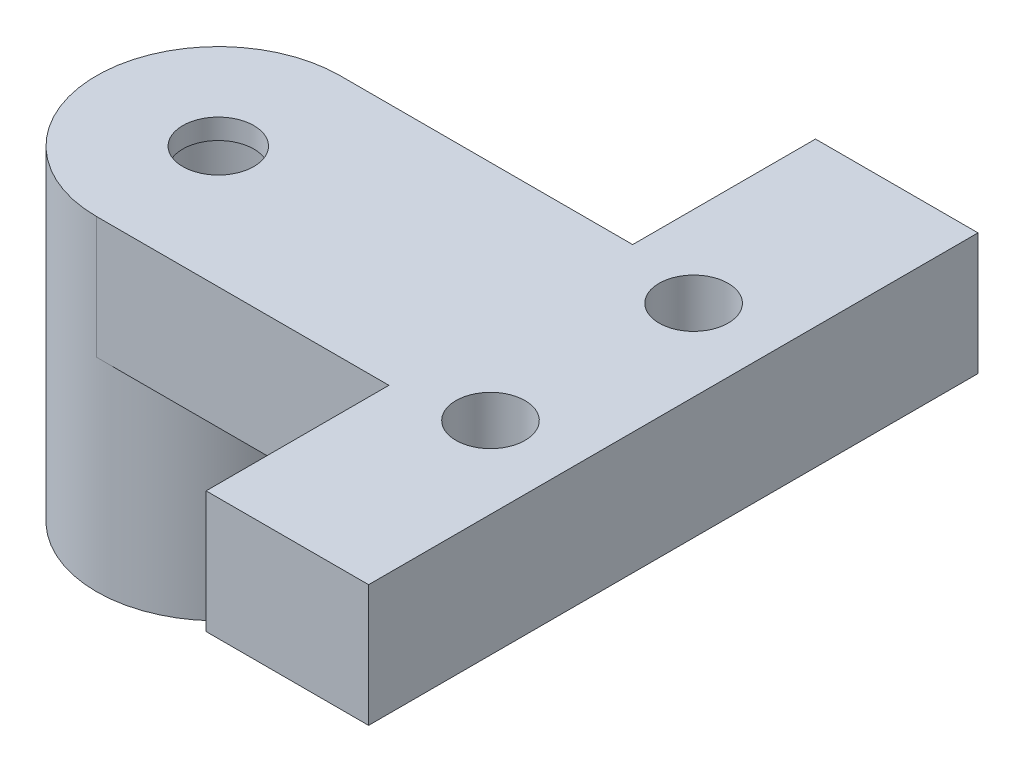
SolidWorks part; units mm, degrees
ref_plane "前视基准面" through (0, 0, 0) normal (0, 0, 1) x (1, 0, 0)
ref_plane "上视基准面" through (0, 0, 0) normal (0, 1, 0) x (1, 0, 0)
ref_plane "右视基准面" through (0, 0, 0) normal (1, 0, 0) x (0, 0, -1)
sketch "草图1" plane through (0, 0, 0) normal (0, 0, 1) x (1, 0, 0)
  line L1 (0, 0) -> (33, 0)
  line L2 (0, 0) -> (0, -6)
  line L3 (0, -6) -> (33, -6)
  line L4 (33, 0) -> (33, -6)
  dimension "D1" = 33
  dimension "D2" = 6
extrude "凸台-拉伸1" add sketch "草图1" along normal blind 30
sketch "草图3" plane through (0, -6, 0) normal (0, -1, 0) x (1, 0, 0)
  line L0 (0, 15) -> (33, 15) construction
  line L1 (0, 30) -> (0, 0) construction
  line L2 (33, 30) -> (33, 0) construction
  circle A0 centre (10.6, 15) radius 6
  dimension "D1" = 12
  dimension "D2" = 22.4
extrude "凸台-拉伸2" add sketch "草图3" along normal blind 10
sketch "草图4" plane through (0, -16, 0) normal (0, -1, 0) x (1, 0, 0)
  circle A0 centre (10.6, 15) radius 3.1
  dimension "D1" = 6.2
extrude "切除-拉伸1" cut sketch "草图4" against normal blind 15
sketch "草图5" plane through (0, -1, 0) normal (0, -1, 0) x (1, 0, 0)
  circle A0 centre (10.6, 15) radius 1.75
  dimension "D1" = 3.5
extrude "切除-拉伸2" cut sketch "草图5" against normal through all
sketch "草图10" plane through (0, 0, 0) normal (0, 0, 1) x (1, 0, 0)
  line L0 (10.6, -16) -> (10.6, 0) construction
  line L1 (4.6, -16) -> (16.6, -16) construction
  line L2 (33, 0) -> (0, 0) construction
  circle A0 centre (10.6, -11) radius 1
  dimension "D1" = 2
  dimension "D2" = 5
extrude "凸台-拉伸3" add sketch "草图10" along normal up to next
hole_wizard "M4 螺纹孔7" positions "3D草图8" profile "草图16" tap size "M4" standard "GB"
sketch3d "3D草图8"
  line L0 (10.6, -11, 9.0839) -> (10.6, -11, 0) construction
  point P0 (10.6, -11, 0)
cosmetic thread "孔螺蚊线7" parameters "D1"=11.3562, "D2"=4
sketch "草图16" plane through (10.6, -11, 0) normal (1, 0, 0) x (0, 1, 0)
  line L0 (0, 0) -> (0, 15.9914)
  line L1 (0, 15.9914) -> (1.65, 15)
  line L2 (1.65, 15) -> (1.65, 0)
  line L5 (1.65, 0) -> (0, 0)
  line L10 (0, 15.9914) -> (-1.65, 15) construction
  line L11 (0, -6.35) -> (0, 107.95) construction
  dimension "螺纹孔钻头直径" = 3.3
  dimension "螺纹孔钻头深度" = 15
  dimension "导头角度" = 118
sketch "草图17" plane through (0, 0, 0) normal (1, 0, 0) x (0, 0, -1)
  line L0 (-15, 5.4069) -> (-15, -30.5116) construction
  line L1 (-21, -16) -> (-9, -16) construction
  circle A0 centre (-15, -11) radius 1.5
  dimension "D1" = 3
  dimension "D2" = 5
extrude "凸台-拉伸4" add sketch "草图17" along normal up to next
hole_wizard "M4 螺纹孔8" positions "3D草图9" profile "草图18" tap size "M4" standard "GB"
sketch3d "3D草图9"
  line L0 (4.7905, -11, 15) -> (0, -11, 15) construction
  point P0 (0, -11, 15)
sketch "草图18" plane through (0, -11, 15) normal (0, 1, 0) x (0, 0, 1)
  line L0 (0, 0) -> (0, 13.9914)
  line L1 (0, 13.9914) -> (1.65, 13)
  line L2 (1.65, 13) -> (1.65, 0)
  line L5 (1.65, 0) -> (0, 0)
  line L10 (0, 13.9914) -> (-1.65, 13) construction
  line L11 (0, -6.35) -> (0, 107.95) construction
  dimension "螺纹孔钻头直径" = 3.3
  dimension "螺纹孔钻头深度" = 13
  dimension "导头角度" = 118
cosmetic thread "孔螺蚊线9" parameters "D1"=7.4562, "D2"=4
sketch "草图19" plane through (0, -6, 0) normal (0, -1, 0) x (1, 0, 0)
  line L0 (33, 15) -> (0, 15) construction
  line L1 (33, 30) -> (33, 0) construction
  line L2 (0, 30) -> (0, 0) construction
  line L3 (25, 30) -> (25, 0) construction
  line L4 (0, 30) -> (33, 30) construction
  line L5 (0, 0) -> (33, 0) construction
  line L6 (29, 30) -> (29, 0) construction
  circle A0 centre (29, 20) radius 2.5
  circle A1 centre (29, 10) radius 2.5
  dimension "D3" = 5
  dimension "D4" = 5
  dimension "D1" = 8
  dimension "D2" = 4
  dimension "D5" = 5
  dimension "D6" = 5
hole_wizard "打孔尺寸(%根据)内六角圆柱头螺钉的类型1" positions "3D草图11" profile "草图21" counterbore size "M3" standard "GB" end condition through all
sketch3d "3D草图11"
  point P0 (29, -6, 20)
  point P3 (29, -6, 10)
sketch "草图21" plane through (29, -6, 20) normal (1, 0, 0) x (0, 0, -1)
  line L0 (0, 0) -> (0, 6)
  line L1 (0, 6) -> (1.7, 6)
  line L3 (1.7, 6) -> (1.7, 3.4)
  line L4 (1.7, 3.4) -> (3, 3.4)
  line L5 (3, 3.4) -> (3, 0)
  line L7 (3, 0) -> (0, 0)
  line L11 (0, -6.35) -> (0, 107.95) construction
  dimension "通孔孔直径" = 3.4
  dimension "通孔孔深度" = 6
  dimension "柱形沉头孔直径" = 6
  dimension "柱形沉头孔深度" = 3.4
sketch "草图22" plane through (0, -6, 0) normal (0, -1, 0) x (1, 0, 0)
  line L0 (25, 30) -> (25, 0) construction
  line L1 (0, 30) -> (33, 30) construction
  line L2 (0, 0) -> (33, 0) construction
  line L3 (33, 30) -> (33, 0) construction
  line L4 (10.6, 21) -> (25, 21)
  line L5 (25, 21) -> (25, 30)
  line L6 (25, 30) -> (0, 30)
  line L7 (0, 30) -> (0, 0)
  line L8 (0, 0) -> (25, 0)
  line L9 (25, 0) -> (25, 9)
  line L10 (25, 9) -> (10.6, 9)
  arc A0 (10.6, 21) -> (10.6, 9) centre (10.6, 15) ccw
  dimension "D2" = 6
  dimension "D1" = 8
extrude "切除-拉伸3" cut sketch "草图22" against normal through all
